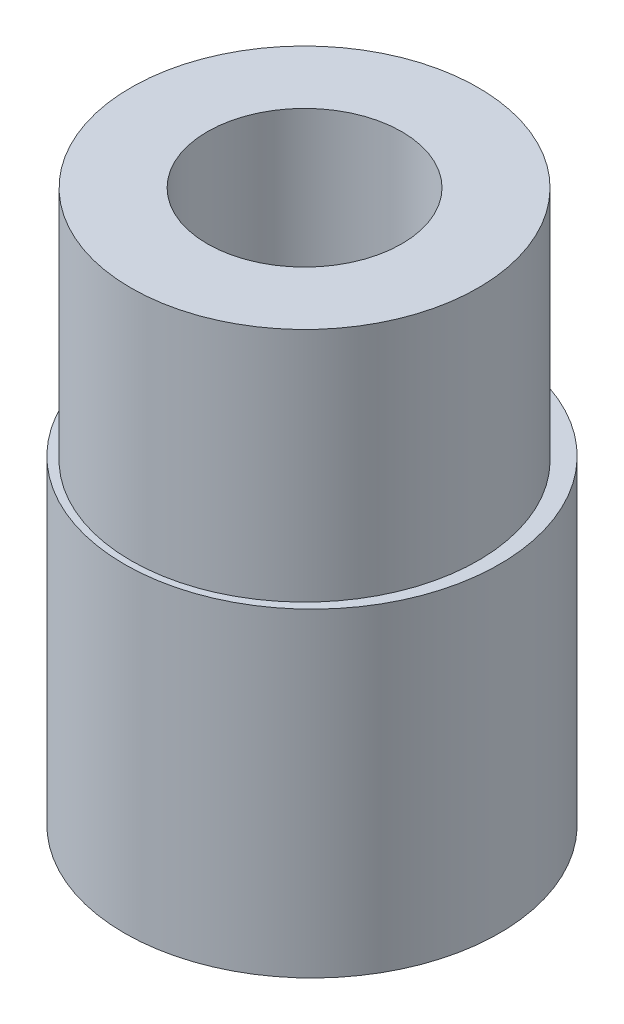
SolidWorks part; units mm, degrees
ref_plane "Front Plane" through (0, 0, 0) normal (0, 0, 1) x (1, 0, 0)
ref_plane "Top Plane" through (0, 0, 0) normal (0, 1, 0) x (1, 0, 0)
ref_plane "Right Plane" through (0, 0, 0) normal (1, 0, 0) x (0, 0, -1)
sketch "Sketch1" plane through (0, 0, 0) normal (0, 1, 0) x (1, 0, 0)
  circle A0 centre (0, 0) radius 3.175
  dimension "D1" = 6.35
extrude "Boss-Extrude1" add sketch "Sketch1" along normal blind 4.318
sketch "Sketch2" plane through (0, 4.318, 0) normal (0, 1, 0) x (1, 0, 0)
  circle A0 centre (0, 0) radius 1.778
  dimension "D1" = 3.556
extrude "Cut-Extrude1" cut sketch "Sketch2" against normal blind 3.048
sketch "Sketch4" plane through (0, 0, 0) normal (0, -1, 0) x (1, 0, 0)
  circle A0 centre (0, -0.1361) radius 3.429
extrude "Boss-Extrude2" add sketch "Sketch4" along normal blind 5.842
sketch "Sketch5" plane through (0, -5.842, 0) normal (0, -1, 0) x (1, 0, 0)
  circle A0 centre (0, 0) radius 2.794
  dimension "D1" = 5.588
extrude "Cut-Extrude2" cut sketch "Sketch5" against normal blind 4.826
